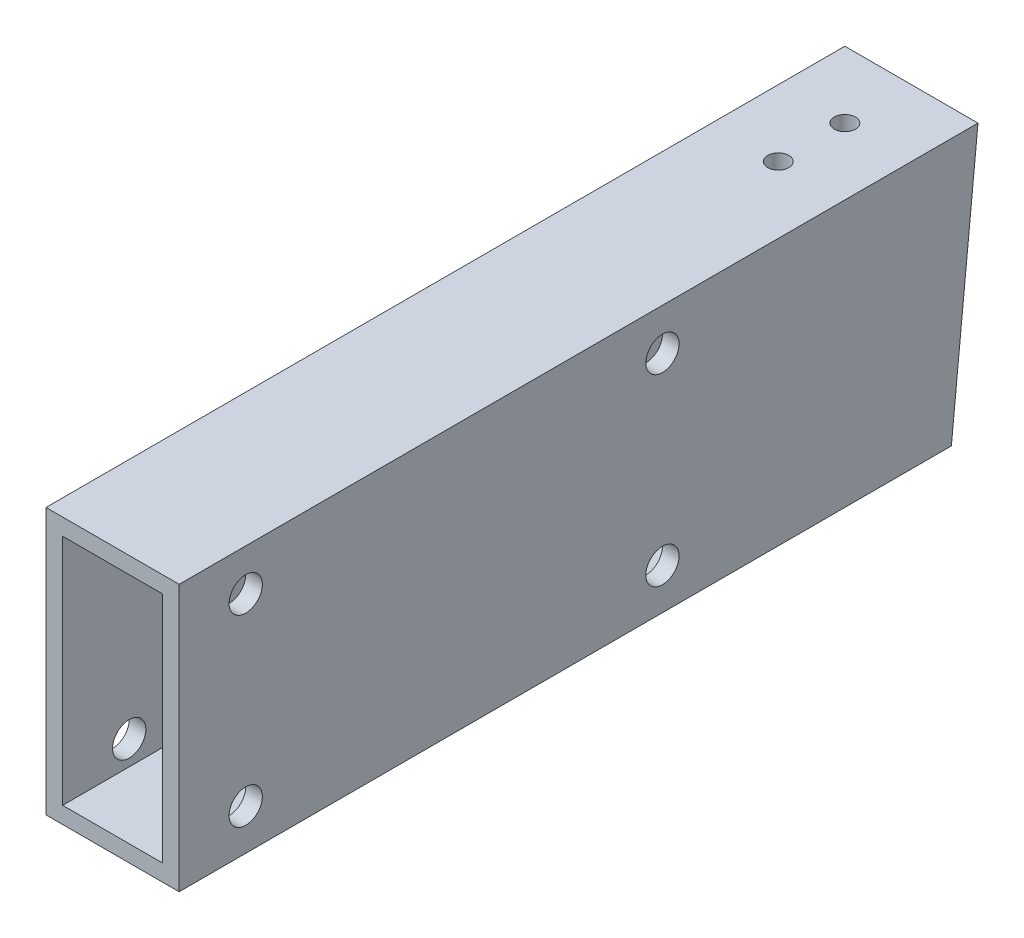
SolidWorks part; units mm, degrees
ref_plane "Front Plane" through (0, 0, 0) normal (0, 0, 1) x (1, 0, 0)
ref_plane "Top Plane" through (0, 0, 0) normal (0, 1, 0) x (1, 0, 0)
ref_plane "Right Plane" through (0, 0, 0) normal (1, 0, 0) x (0, 0, -1)
sketch "Sketch1" plane through (0, 0, 0) normal (0, 0, 1) x (1, 0, 0)
  line L1 (12.7, 25.4) -> (-12.7, 25.4)
  line L2 (12.7, 25.4) -> (12.7, -25.4)
  line L3 (12.7, -25.4) -> (-12.7, -25.4)
  line L4 (-12.7, 25.4) -> (-12.7, -25.4)
  line L5 (12.7, 25.4) -> (-12.7, -25.4) construction
  line L6 (12.7, -25.4) -> (-12.7, 25.4) construction
  point P0 (0, 0)
  dimension "D1" = 25.4
  dimension "D2" = 50.8
extrude "Boss-Extrude1" add sketch "Sketch1" along normal mid plane 152.4
hole_wizard "1/4 (0.25) Diameter Hole1" positions "Sketch4" profile "Sketch3" hole size "1/4" standard "ANSI Inch" end condition through all
sketch "Sketch4" plane through (12.7, 0, 0) normal (1, 0, 0) x (0, 0, -1)
  line L0 (-76.2, -25.4) -> (-76.2, 25.4) construction
  line L1 (-76.2, 25.4) -> (76.2, 25.4) construction
  point P0 (-63.5, 17.4625)
  point P9 (16.002, 17.4625)
  point P10 (16.002, -17.5895)
  point P11 (-63.5, -17.5895)
  dimension "D3" = 12.7
  dimension "D4" = 7.9375
  dimension "D1" = 2
  dimension "D2" = 2
sketch "Sketch3" plane through (12.7, 17.4625, 63.5) normal (0, 1, 0) x (0, 0, -1)
  line L0 (0, 0) -> (0, 25.4)
  line L1 (0, 25.4) -> (3.175, 25.4)
  line L2 (3.175, 25.4) -> (3.175, 0)
  line L5 (3.175, 0) -> (0, 0)
  line L11 (0, -6.35) -> (0, 107.95) construction
  dimension "Thru Hole Dia." = 6.35
  dimension "Thru Hole Depth" = 25.4
hole_wizard "#10-32 Tapped Hole1" positions "Sketch6" profile "Sketch5" tap size "#10-32" standard "ANSI Inch"
sketch "Sketch6" plane through (0, 25.4, 0) normal (0, 1, 0) x (1, 0, 0)
  line L0 (12.7, 76.2) -> (-12.7, 76.2) construction
  line L1 (12.7, -76.2) -> (12.7, 76.2) construction
  point P0 (0, 63.5)
  point P9 (0, 50.8)
  dimension "D2" = 12.7
  dimension "D3" = 12.7
  dimension "D1" = 2
sketch "Sketch5" plane through (0, 25.4, -63.5) normal (1, 0, 0) x (0, 0, 1)
  line L0 (0, 0) -> (0, 14.9293)
  line L1 (0, 14.9293) -> (2.0193, 13.716)
  line L2 (2.0193, 13.716) -> (2.0193, 0)
  line L5 (2.0193, 0) -> (0, 0)
  line L10 (0, 14.9293) -> (-2.0193, 13.716) construction
  line L11 (0, -6.35) -> (0, 107.95) construction
  dimension "Tap Drill Dia." = 4.0386
  dimension "Tap Drill Depth" = 13.716
  dimension "Drill Angle" = 118
sketch "Sketch8" plane through (12.7, 0, 0) normal (1, 0, 0) x (0, 0, -1)
  line L0 (76.2, 25.4) -> (71.12, -25.4)
  line L1 (-76.2, -25.4) -> (76.2, -25.4) construction
  line L2 (71.12, -25.4) -> (76.2, -25.4)
  line L3 (76.2, -25.4) -> (76.2, 25.4)
  dimension "D1" = 5.08
extrude "Cut-Extrude1" cut sketch "Sketch8" against normal through all
sketch "Sketch9" plane through (0, 0, 76.2) normal (0, 0, 1) x (1, 0, 0)
  line L14 (-9.525, -22.225) -> (9.525, -22.225)
  line L15 (-9.525, 22.225) -> (-9.525, -22.225)
  line L16 (9.525, -22.225) -> (9.525, 22.225)
  line L17 (9.525, 22.225) -> (-9.525, 22.225)
  line L18 (-9.525, -22.225) -> (9.525, -22.225)
  line L19 (-9.525, 22.225) -> (-9.525, -22.225)
  line L20 (9.525, -22.225) -> (9.525, 22.225)
  line L21 (9.525, 22.225) -> (-9.525, 22.225)
  dimension "D1" = 3.175
extrude "Cut-Extrude2" cut sketch "Sketch9" against normal through all
